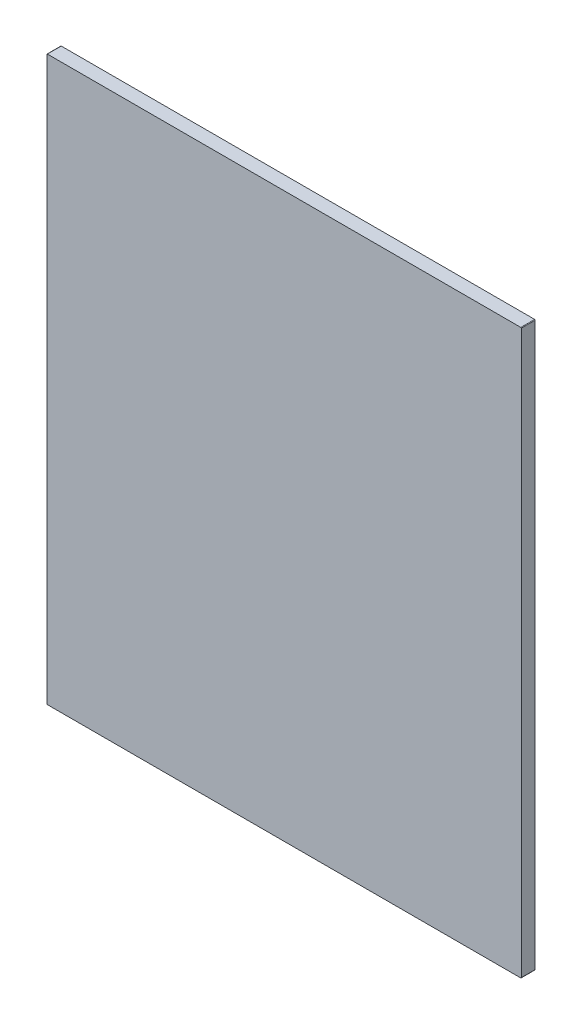
SolidWorks part; units mm, degrees
material "PE High Density"
ref_plane "Front Plane" through (0, 0, 0) normal (0, 0, 1) x (1, 0, 0)
ref_plane "Top Plane" through (0, 0, 0) normal (0, 1, 0) x (1, 0, 0)
ref_plane "Right Plane" through (0, 0, 0) normal (1, 0, 0) x (0, 0, -1)
sketch "Sketch1" plane through (0, 0, 0) normal (0, 0, 1) x (1, 0, 0)
  line L5 (0, 0) -> (217.17, 0)
  line L6 (0, 0) -> (0, 257.937)
  line L7 (0, 257.937) -> (217.17, 257.937)
  line L30 (217.17, 0) -> (217.17, 257.937)
  dimension "D1" = 257.937
  dimension "D2" = 217.17
extrude "Boss-Extrude3" add sketch "Sketch1" along normal blind 6.35
fillet "Fillet1" radius 0.254 4 edges at (217.17, 0, 3.175) (0, 0, 3.175) (0, 257.937, 3.175) (217.17, 257.937, 3.175)
